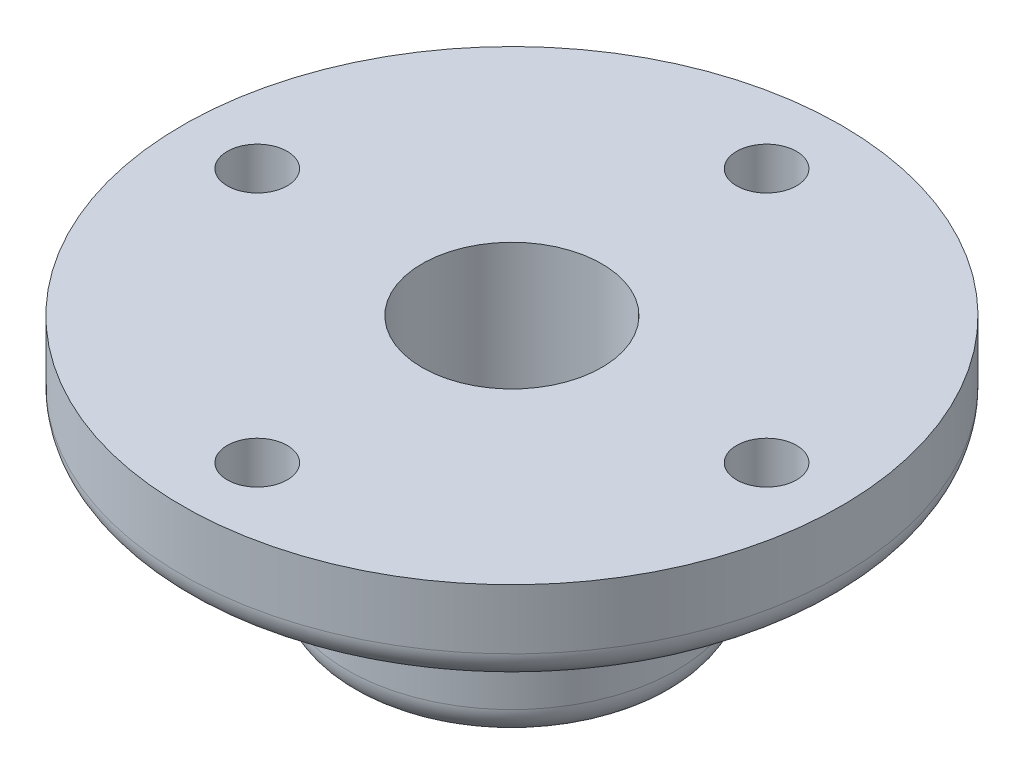
SolidWorks part; units mm, degrees
ref_plane "Front Plane" through (0, 0, 0) normal (0, 0, 1) x (1, 0, 0)
ref_plane "Top Plane" through (0, 0, 0) normal (0, 1, 0) x (1, 0, 0)
ref_plane "Right Plane" through (0, 0, 0) normal (1, 0, 0) x (0, 0, -1)
sketch "Sketch1" plane through (0, 0, 0) normal (1, 0, 0) x (0, 0, -1)
  line L0 (0, 0) -> (0, 53.975)
  line L1 (0, 53.975) -> (69.85, 53.975)
  line L2 (69.85, 53.975) -> (69.85, 41.275)
  line L3 (63.5, 34.925) -> (41.275, 34.925)
  line L4 (34.925, 28.575) -> (34.925, 6.35)
  line L5 (28.575, 0) -> (0, 0)
  arc A0 (28.575, 0) -> (34.925, 6.35) centre (28.575, 6.35) ccw
  arc A1 (69.85, 41.275) -> (63.5, 34.925) centre (63.5, 41.275) cw
  arc A2 (34.925, 28.575) -> (41.275, 34.925) centre (41.275, 28.575) cw
  point P9 (34.925, 0)
  point P12 (69.85, 34.925)
  dimension "D5" = 6.35
  dimension "D1" = 19.05
  dimension "D2" = 69.85
  dimension "D3" = 53.975
  dimension "D4" = 34.925
revolve "Revolve1" add sketch "Sketch1" angle 360 about L0
sketch "Sketch2" plane through (0, 53.975, 0) normal (0, 1, 0) x (1, 0, 0)
  circle A0 centre (0, 0) radius 19.05
  circle A1 centre (0, 0) radius 53.975 construction
  circle A2 centre (0, 53.975) radius 6.35
  circle A3 centre (53.975, 0) radius 6.35
  circle A4 centre (0, -53.975) radius 6.35
  circle A5 centre (-53.975, 0) radius 6.35
  point P6 (0, 0)
  point P7 (0, 0)
  point P8 (0, 0)
  point P15 (0, 0)
  point P16 (53.975, 0)
  point P17 (53.975, 0)
  point P18 (53.975, 0)
  point P19 (0, 0)
  point P20 (0, 0)
  point P21 (0, 0)
  dimension "D1" = 107.95
  dimension "D2" = 38.1
  dimension "D3" = 12.7
  dimension "D4" = 4
extrude "Cut-Extrude1" cut sketch "Sketch2" against normal through all
